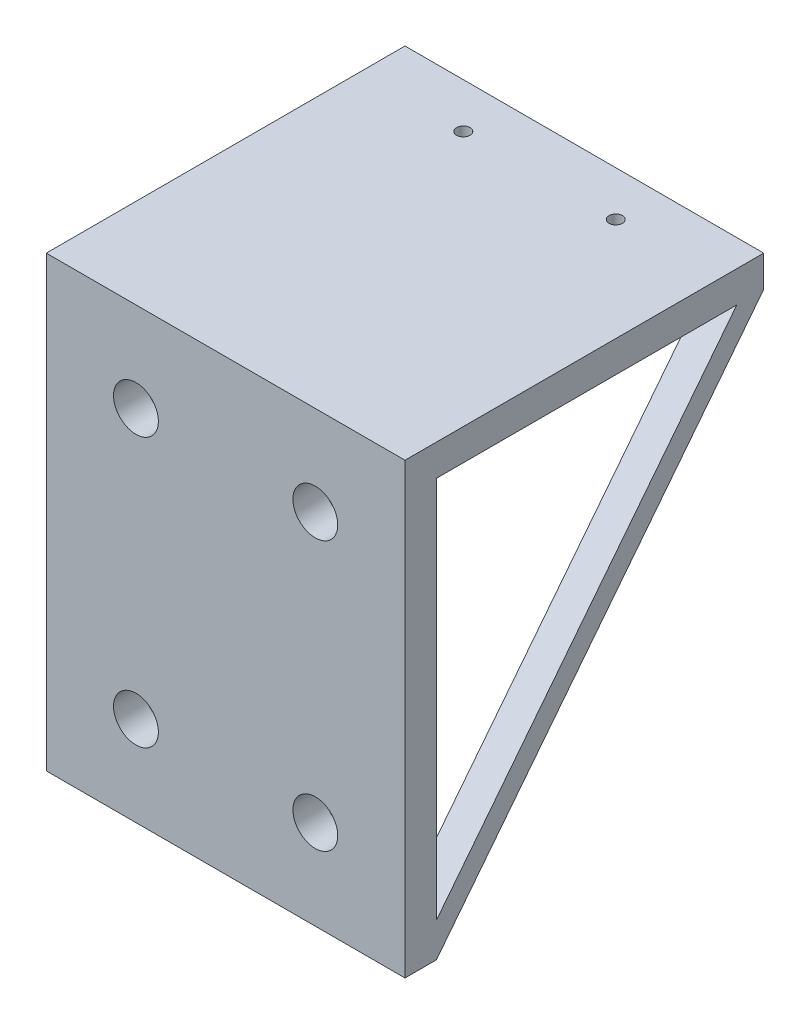
SolidWorks part; units mm, degrees
ref_plane "Front Plane" through (0, 0, 0) normal (0, 0, 1) x (1, 0, 0)
ref_plane "Top Plane" through (0, 0, 0) normal (0, 1, 0) x (1, 0, 0)
ref_plane "Right Plane" through (0, 0, 0) normal (1, 0, 0) x (0, 0, -1)
sketch "Sketch1" plane through (0, 0, 0) normal (0, 0, 1) x (1, 0, 0)
  line L1 (40, -50) -> (-40, -50)
  line L2 (40, -50) -> (40, 50)
  line L3 (40, 50) -> (-40, 50)
  line L4 (-40, -50) -> (-40, 50)
  line L5 (40, -50) -> (-40, 50) construction
  line L6 (40, 50) -> (-40, -50) construction
  point P0 (0, 0)
  dimension "D1" = 80
  dimension "D2" = 100
extrude "Boss-Extrude1" add sketch "Sketch1" along normal blind 7
sketch "Sketch2" plane through (0, 0, 0) normal (0, 0, -1) x (-1, 0, 0)
  line L0 (-40, 50) -> (40, 50) construction
  line L1 (-40, -50) -> (-40, 50) construction
  line L2 (0, 63.5648) -> (0, -71.5229) construction
  line L3 (-70.479, 0) -> (83.676, 0) construction
  circle A0 centre (-20, 30) radius 5
  circle A1 centre (20, 30) radius 5
  circle A2 centre (20, -30) radius 5
  circle A3 centre (-20, -30) radius 5
  dimension "D1" = 10
  dimension "D2" = 20
  dimension "D3" = 20
extrude "Cut-Extrude1" cut sketch "Sketch2" against normal blind 7
sketch "Sketch4" plane through (0, 50, 0) normal (0, 1, 0) x (1, 0, 0)
  line L1 (-40, -7) -> (40, -7)
  line L2 (-40, -7) -> (-40, 73)
  line L3 (-40, 73) -> (40, 73)
  line L4 (40, -7) -> (40, 73)
  dimension "D1" = 80
  dimension "D2" = 80
extrude "Boss-Extrude2" add sketch "Sketch4" against normal blind 7
sketch "Sketch5" plane through (40, 0, 0) normal (1, 0, 0) x (0, 0, -1)
  line L0 (0, -50) -> (73, 43)
  line L1 (0, -50) -> (-6, -50)
  line L2 (73, 43) -> (67, 43)
  line L3 (-6, -50) -> (67, 43)
  line L4 (0, 43) -> (73, 43) construction
  dimension "D1" = 6
extrude "Boss-Extrude4" add sketch "Sketch5" against normal blind 7
mirror "Mirror3" about plane through (0, 0, 0) normal (1, 0, 0) of "Boss-Extrude4"
sketch "Sketch6" plane through (0, 50, 0) normal (0, 1, 0) x (1, 0, 0)
  line L0 (40, 73) -> (-40, 73) construction
  line L1 (-40, -7) -> (-40, 73) construction
  circle A0 centre (-17, 63) radius 1.5
  circle A1 centre (17, 63) radius 1.5
  dimension "D2" = 3
  dimension "D5" = 3
  dimension "D1" = 10
  dimension "D3" = 34
  dimension "D4" = 23
  dimension "D6" = 10
extrude "Cut-Extrude2" cut sketch "Sketch6" against normal blind 7
